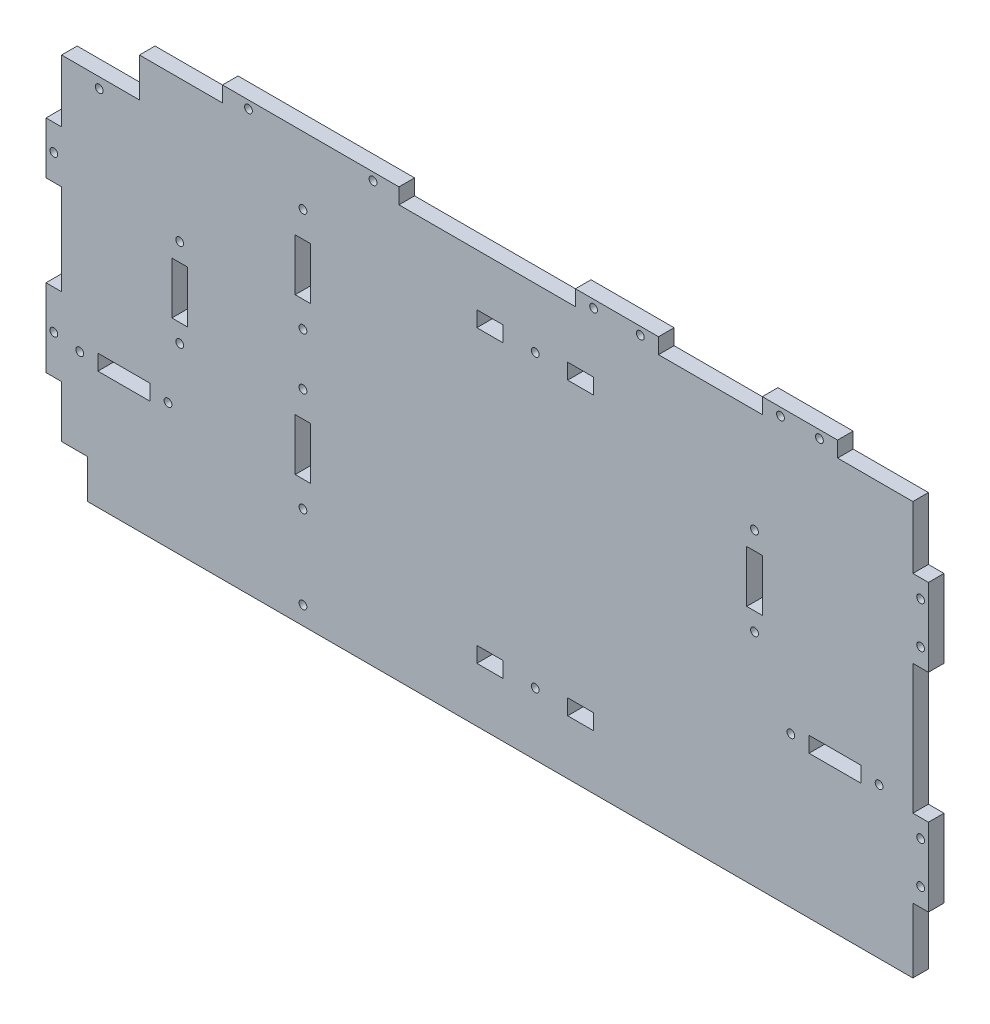
SolidWorks part; units mm, degrees
ref_plane "Plan de face" through (0, 0, 0) normal (0, 0, 1) x (1, 0, 0)
ref_plane "Plan de dessus" through (0, 0, 0) normal (0, 1, 0) x (1, 0, 0)
ref_plane "Plan de droite" through (0, 0, 0) normal (1, 0, 0) x (0, 0, -1)
sketch "Esquisse1" plane through (0, 0, 0) normal (0, 0, 1) x (1, 0, 0)
  line L1 (0, 0) -> (-340, 0)
  line L2 (0, 0) -> (0, 165)
  line L3 (0, 165) -> (-340, 165)
  line L4 (-340, 0) -> (-340, 165)
  dimension "D1" = 165
  dimension "D2" = 340
extrude "Boss.-Extru.1" add sketch "Esquisse1" along normal blind 6
sketch "Esquisse2" plane through (0, 0, 6) normal (0, 0, 1) x (1, 0, 0)
  line L0 (0, 0) -> (0, 165) construction
  line L1 (0, 165) -> (-340, 165) construction
  line L2 (0, 165) -> (0, 135)
  line L3 (0, 165) -> (-340, 165) construction
  line L4 (0, 135) -> (-6, 135)
  line L5 (-6, 135) -> (-6, 159)
  line L6 (-340, 165) -> (-272, 165)
  line L7 (-334, 65) -> (-334, 100)
  line L8 (-340, 65) -> (-334, 65)
  line L9 (-334, 100) -> (-340, 100)
  line L10 (-70, 112) -> (-64, 112)
  line L11 (-70, 112) -> (-70, 92)
  line L12 (-70, 92) -> (-64, 92)
  line L13 (-334, 159) -> (-272, 159)
  line L14 (-272, 165) -> (-272, 159)
  line L15 (-204, 165) -> (-136, 165)
  line L16 (-204, 165) -> (-204, 159)
  line L17 (-204, 159) -> (-136, 159)
  line L18 (0, 0) -> (0, 165) construction
  line L19 (0, 0) -> (-6, 0)
  line L20 (0, 0) -> (0, 25)
  line L21 (0, 25) -> (-6, 25)
  line L22 (-136, 165) -> (-136, 159)
  line L23 (0, 165) -> (-35, 165)
  line L24 (-340, 0) -> (-334, 0)
  line L25 (-104, 159) -> (-64, 159)
  line L26 (-104, 165) -> (-104, 159)
  line L27 (-64, 112) -> (-64, 92)
  line L28 (-6, 0) -> (-6, 25)
  line L29 (0, 105) -> (-6, 105)
  line L30 (0, 105) -> (0, 55)
  line L31 (0, 55) -> (-6, 55)
  line L32 (-6, 105) -> (-6, 55)
  line L33 (-340, 0) -> (-340, 35)
  line L34 (-340, 35) -> (-334, 35)
  line L35 (-334, 0) -> (-334, 35)
  line L36 (-26, 61) -> (-46, 61)
  line L37 (-26, 61) -> (-26, 55)
  line L38 (-26, 55) -> (-46, 55)
  line L39 (-46, 61) -> (-46, 55)
  line L40 (-340, 165) -> (-340, 0) construction
  line L41 (-340, 100) -> (-340, 65)
  line L42 (-334, 159) -> (-334, 120)
  line L43 (-334, 120) -> (-340, 120)
  line L44 (-340, 120) -> (-340, 165)
  line L45 (-64, 159) -> (-64, 165)
  line L46 (-64, 165) -> (-104, 165)
  line L50 (-6, 159) -> (-35, 159)
  line L51 (-35, 165) -> (-35, 159)
  dimension "D3" = 6
  dimension "D4" = 62
  dimension "D5" = 35
  dimension "D6" = 68
  dimension "D7" = 29
  dimension "D8" = 6
  dimension "D9" = 70
  dimension "D10" = 6
  dimension "D11" = 6
  dimension "D12" = 6
  dimension "D13" = 6
  dimension "D14" = 68
  dimension "D15" = 6
  dimension "D16" = 30
  dimension "D17" = 37
  dimension "D18" = 6
  dimension "D19" = 20
  dimension "D20" = 25
  dimension "D21" = 30
  dimension "D22" = 35
  dimension "D23" = 6
  dimension "D24" = 20
  dimension "D25" = 6
  dimension "D26" = 26
  dimension "D27" = 40
  dimension "D28" = 30
  dimension "D29" = 20
  dimension "D30" = 35
  dimension "D31" = 6
  dimension "D32" = 104
  dimension "D33" = 30
extrude "Enlèv. mat.-Extru.1" cut sketch "Esquisse2" against normal blind 6
sketch "Esquisse3" plane through (0, 0, 0) normal (0, 0, -1) x (-1, 0, 0)
  line L0 (340, 65) -> (340, 35) construction
  line L1 (238, 109) -> (244, 109)
  line L2 (238, 109) -> (238, 129)
  line L3 (238, 129) -> (244, 129)
  line L4 (244, 109) -> (244, 129)
  line L5 (340, 65) -> (340, 35) construction
  line L6 (340, 65) -> (340, 35) construction
  line L7 (238, 69) -> (244, 69)
  line L8 (238, 69) -> (238, 49)
  line L9 (238, 49) -> (244, 49)
  line L10 (244, 69) -> (244, 49)
  line L11 (204, 165) -> (272, 165) construction
  line L12 (285.5, 77.5) -> (291.5, 77.5)
  line L13 (285.5, 77.5) -> (285.5, 97.5)
  line L14 (285.5, 97.5) -> (291.5, 97.5)
  line L15 (291.5, 77.5) -> (291.5, 97.5)
  line L16 (340, 120) -> (334, 120) construction
  line L17 (204, 165) -> (272, 165) construction
  line L18 (300, 51.5) -> (320, 51.5)
  line L19 (300, 51.5) -> (300, 45.5)
  line L20 (300, 45.5) -> (320, 45.5)
  line L21 (320, 51.5) -> (320, 45.5)
  line L22 (334, 159) -> (304, 159)
  line L23 (334, 159) -> (334, 144)
  line L24 (334, 144) -> (304, 144)
  line L25 (304, 159) -> (304, 144)
  line L29 (340, 65) -> (340, 35) construction
  line L31 (334, 159) -> (272, 159) construction
  point P12 (340, 50)
  dimension "D1" = 6
  dimension "D2" = 20
  dimension "D3" = 96
  dimension "D4" = 36
  dimension "D5" = 6
  dimension "D6" = 40
  dimension "D7" = 96
  dimension "D8" = 20
  dimension "D9" = 20
  dimension "D10" = 6
  dimension "D11" = 48.5
  dimension "D12" = 67.5
  dimension "D13" = 107.5
  dimension "D14" = 24
  dimension "D15" = 20
  dimension "D16" = 30
  dimension "D17" = 6
  dimension "D20" = 20
extrude "Enlèv. mat.-Extru.2" cut sketch "Esquisse3" against normal blind 10
sketch "Esquisse5" plane through (0, 0, 0) normal (0, 0, -1) x (-1, 0, 0)
  line L0 (104, 165) -> (136, 165) construction
  line L1 (129, 139) -> (139, 139)
  line L2 (129, 139) -> (129, 133)
  line L3 (129, 133) -> (139, 133)
  line L4 (139, 139) -> (139, 133)
  line L5 (164, 133) -> (174, 133)
  line L6 (164, 133) -> (164, 139)
  line L7 (164, 139) -> (174, 139)
  line L8 (174, 133) -> (174, 139)
  line L10 (129, 27) -> (139, 27)
  line L11 (129, 27) -> (129, 21)
  line L12 (340, 65) -> (340, 35) construction
  line L13 (129, 21) -> (139, 21)
  line L14 (139, 27) -> (139, 21)
  line L15 (104, 165) -> (136, 165) construction
  line L16 (164, 27) -> (174, 27)
  line L17 (164, 27) -> (164, 21)
  line L18 (164, 21) -> (174, 21)
  line L19 (174, 27) -> (174, 21)
  line L20 (204, 165) -> (272, 165) construction
  line L21 (340, 65) -> (340, 35) construction
  line L22 (204, 159) -> (136, 159) construction
  circle A0 centre (151.5, 136) radius 1.5
  circle A1 centre (151.5, 24) radius 1.5
  dimension "D9" = 3
  dimension "D14" = 138
  dimension "D21" = 3
  dimension "D22" = 3
  dimension "D11" = 3
  dimension "D1" = 6
  dimension "D2" = 10
  dimension "D3" = 6
  dimension "D4" = 10
  dimension "D5" = 25
  dimension "D6" = 26
  dimension "D7" = 26
  dimension "D8" = 166
  dimension "D10" = 12.5
  dimension "D12" = 6
  dimension "D13" = 138
  dimension "D15" = 25
  dimension "D16" = 12.5
  dimension "D17" = 166
  dimension "D18" = 10
  dimension "D19" = 10
  dimension "D20" = 138
extrude "Enlèv. mat.-Extru.4" cut sketch "Esquisse5" against normal blind 6
sketch "Esquisse7" plane through (0, 0, 0) normal (0, 0, -1) x (-1, 0, 0)
  line L0 (241, 45.9831) -> (241, 125.9831) construction
  line L1 (340, 120) -> (340, 100) construction
  line L2 (334, 0) -> (324, 0)
  line L3 (238, 49) -> (244, 49) construction
  line L4 (244, 69) -> (238, 69) construction
  line L5 (238, 109) -> (244, 109) construction
  line L6 (244, 129) -> (238, 129) construction
  line L7 (204, 165) -> (272, 165) construction
  line L8 (272, 159) -> (272, 165) construction
  line L9 (204, 165) -> (204, 159) construction
  line L18 (46, 61) -> (46, 55) construction
  line L19 (46, 55) -> (26, 55) construction
  line L20 (26, 55) -> (26, 61) construction
  line L21 (70, 112) -> (70, 92) construction
  line L22 (70, 92) -> (64, 92) construction
  line L23 (64, 112) -> (70, 112) construction
  line L24 (0, 25) -> (0, 55) construction
  line L25 (0, 25) -> (6, 25) construction
  line L26 (6, 55) -> (0, 55) construction
  line L27 (0, 105) -> (0, 135) construction
  line L28 (0, 105) -> (6, 105) construction
  line L29 (6, 135) -> (0, 135) construction
  line L30 (104, 165) -> (104, 159) construction
  line L31 (104, 165) -> (136, 165) construction
  line L32 (136, 159) -> (136, 165) construction
  line L33 (334, 0) -> (6, 0) construction
  line L34 (238, 69) -> (238, 49) construction
  line L35 (300, 51.5) -> (300, 45.5) construction
  line L36 (300, 45.5) -> (320, 45.5) construction
  line L37 (320, 51.5) -> (300, 51.5) construction
  line L38 (320, 45.5) -> (320, 51.5) construction
  line L39 (340, 65) -> (340, 35) construction
  line L40 (334, 35) -> (340, 35) construction
  line L41 (35, 165) -> (35, 159) construction
  line L42 (35, 165) -> (64, 165) construction
  line L43 (64, 159) -> (64, 165) construction
  line L45 (291.5, 97.5) -> (285.5, 97.5) construction
  line L46 (291.5, 77.5) -> (291.5, 97.5) construction
  line L47 (285.5, 97.5) -> (285.5, 77.5) construction
  line L48 (285.5, 77.5) -> (291.5, 77.5) construction
  line L49 (334, 0) -> (334, 15)
  line L50 (334, 15) -> (324, 15)
  line L51 (324, 0) -> (324, 15)
  line L52 (334, 100) -> (340, 100) construction
  circle A0 centre (337, 50) radius 1.5
  circle A1 centre (319.5, 140) radius 1.5
  circle A2 centre (42, 162) radius 1.5
  circle A3 centre (293, 48.5) radius 1.5
  circle A4 centre (327, 48.5) radius 1.5
  circle A5 centre (288.5, 70.5) radius 1.5
  circle A6 centre (288.5, 104.5) radius 1.5
  circle A7 centre (241, 39) radius 1.5
  circle A8 centre (241, 79) radius 1.5
  circle A9 centre (241, 99) radius 1.5
  circle A10 centre (241, 139) radius 1.5
  circle A11 centre (241, 7) radius 1.5
  circle A12 centre (57, 162) radius 1.5
  circle A13 centre (262, 162) radius 1.5
  circle A14 centre (214, 162) radius 1.5
  circle A15 centre (111, 162) radius 1.5
  circle A16 centre (138, 162) radius 1.5
  circle A17 centre (129, 162) radius 1.5
  circle A18 centre (67, 85) radius 1.5
  circle A19 centre (67, 119) radius 1.5
  circle A20 centre (53, 58) radius 1.5
  circle A21 centre (19, 58) radius 1.5
  circle A22 centre (3, 32) radius 1.505
  circle A23 centre (3, 48) radius 1.5
  circle A24 centre (3, 112) radius 1.5
  circle A25 centre (3, 128) radius 1.5
  circle A30 centre (337, 110) radius 1.5
  point P108 (3, 55)
  dimension "D1" = 3.01
  dimension "D2" = 3
  dimension "D3" = 3
  dimension "D4" = 3
  dimension "D5" = 3
  dimension "D6" = 3
  dimension "D7" = 3
  dimension "D8" = 3
  dimension "D9" = 3
  dimension "D10" = 3
  dimension "D11" = 3
  dimension "D16" = 3
  dimension "D17" = 3
  dimension "D18" = 3
  dimension "D19" = 3
  dimension "D20" = 3
  dimension "D21" = 3
  dimension "D22" = 3
  dimension "D23" = 3
  dimension "D24" = 3
  dimension "D25" = 3
  dimension "D26" = 3
  dimension "D27" = 3
  dimension "D28" = 3
  dimension "D29" = 3
  dimension "D30" = 7
  dimension "D31" = 10
  dimension "D32" = 10
  dimension "D33" = 10
  dimension "D34" = 10
  dimension "D35" = 3
  dimension "D36" = 3
  dimension "D37" = 10
  dimension "D38" = 3
  dimension "D39" = 10
  dimension "D48" = 7
  dimension "D49" = 3
  dimension "D50" = 7
  dimension "D51" = 3
  dimension "D52" = 3
  dimension "D53" = 7
  dimension "D54" = 3
  dimension "D55" = 7
  dimension "D56" = 3
  dimension "D57" = 7
  dimension "D58" = 3
  dimension "D59" = 7
  dimension "D60" = 3
  dimension "D61" = 7
  dimension "D62" = 3
  dimension "D63" = 7
  dimension "D64" = 7
  dimension "D65" = 3
  dimension "D66" = 3
  dimension "D67" = 34
  dimension "D68" = 7
  dimension "D69" = 3
  dimension "D70" = 7
  dimension "D72" = 7
  dimension "D73" = 3
  dimension "D74" = 3
  dimension "D75" = 7
  dimension "D76" = 3
  dimension "D77" = 15
  dimension "D78" = 3
  dimension "D79" = 3
  dimension "D80" = 7
  dimension "D82" = 7
  dimension "D83" = 3
  dimension "D84" = 3
  dimension "D85" = 7
  dimension "D88" = 3
  dimension "D89" = 3
  dimension "D90" = 10
  dimension "D71" = 3
  dimension "D86" = 10
  dimension "D87" = 15
extrude "Enlèv. mat.-Extru.7" cut sketch "Esquisse7" against normal through all
sketch "Esquisse8" plane through (0, 0, 0) normal (0, 0, -1) x (-1, 0, 0)
  circle A0 centre (3, 32) radius 2.995
  circle A1 centre (3, 48) radius 2.995
  circle A2 centre (19, 58) radius 3
  circle A3 centre (3, 112) radius 2.995
  circle A4 centre (3, 128) radius 2.995
  circle A5 centre (53, 58) radius 3
  circle A6 centre (67, 85) radius 3
  circle A7 centre (67, 119) radius 3
  circle A8 centre (111, 162) radius 2.995
  circle A9 centre (42, 162) radius 2.995
  circle A10 centre (129, 162) radius 2.995
  circle A12 centre (151.5, 136) radius 3
  circle A15 centre (151.5, 24) radius 3
  circle A17 centre (214, 162) radius 2.995
  circle A18 centre (57, 162) radius 2.995
  circle A19 centre (262, 162) radius 2.995
  circle A20 centre (241, 139) radius 3
  circle A21 centre (241, 99) radius 3
  circle A22 centre (241, 79) radius 3
  circle A23 centre (241, 39) radius 3
  circle A24 centre (241, 7) radius 3
  circle A25 centre (337, 50) radius 2.995
  circle A26 centre (327, 48.5) radius 3
  circle A27 centre (293, 48.5) radius 3
  circle A28 centre (288.5, 70.5) radius 3
  circle A29 centre (288.5, 104.5) radius 3
  circle A30 centre (319.5, 140) radius 2.995
  circle A32 centre (337, 110) radius 2.995
  dimension "D1" = 5.99
  dimension "D2" = 5.99
  dimension "D3" = 5.99
  dimension "D4" = 5.99
  dimension "D5" = 6
  dimension "D6" = 6
  dimension "D7" = 6
  dimension "D8" = 6
  dimension "D9" = 5.99
  dimension "D10" = 5.99
  dimension "D11" = 5.99
  dimension "D13" = 6
  dimension "D15" = 6
  dimension "D18" = 5.99
  dimension "D19" = 5.99
  dimension "D20" = 5.99
  dimension "D21" = 6
  dimension "D22" = 6
  dimension "D23" = 6
  dimension "D24" = 6
  dimension "D25" = 6
  dimension "D26" = 6
  dimension "D27" = 6
  dimension "D28" = 6
  dimension "D29" = 5.99
  dimension "D30" = 6
  dimension "D31" = 5.99
  dimension "D33" = 5.99
extrude "Enlèv. mat.-Extru.9" cut sketch "Esquisse8" against normal blind 3
